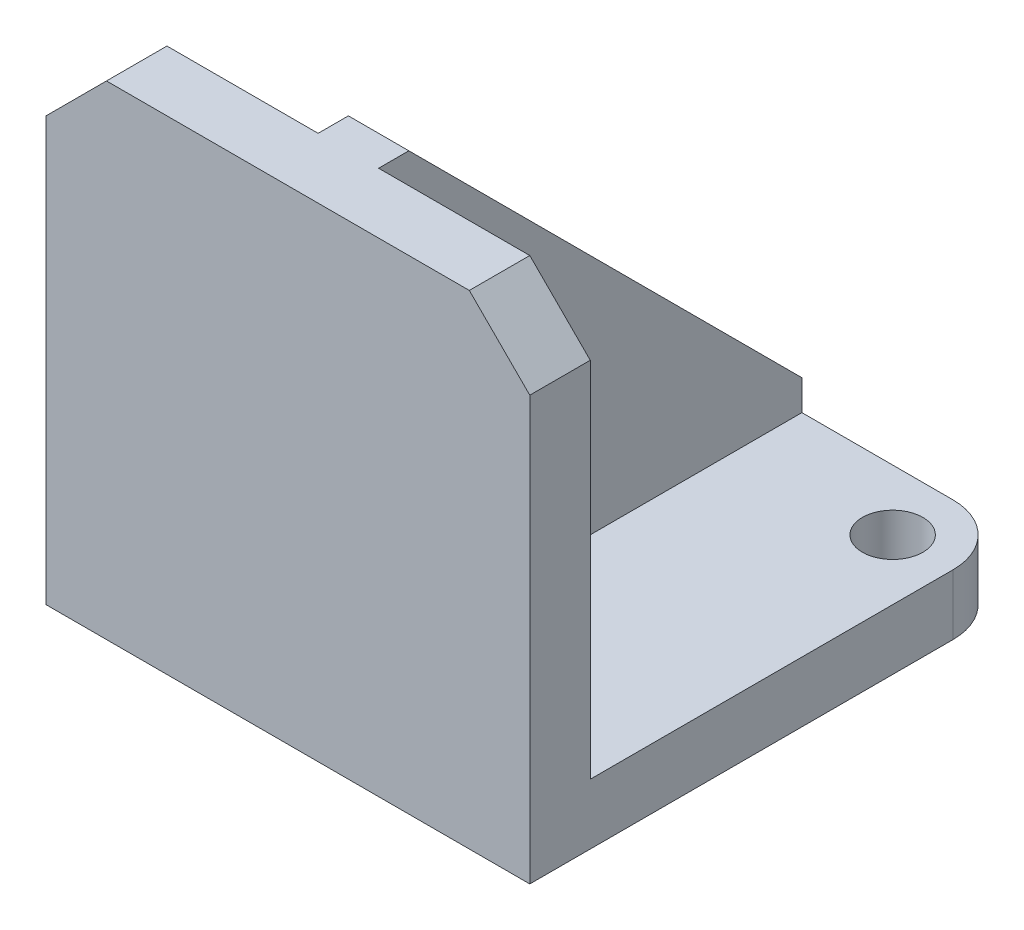
SolidWorks part; units mm, degrees
ref_plane "Front Plane" through (0, 0, 0) normal (0, 0, 1) x (1, 0, 0)
ref_plane "Top Plane" through (0, 0, 0) normal (0, 1, 0) x (1, 0, 0)
ref_plane "Right Plane" through (0, 0, 0) normal (1, 0, 0) x (0, 0, -1)
sketch "Sketch1" plane through (0, 0, 0) normal (1, 0, 0) x (0, 0, -1)
  line L0 (0, 0) -> (80, 0)
  line L1 (0, 80) -> (0, 0)
  line L2 (-13.3901, -27.8014) -> (-13.844, -27.8014)
  line L3 (10, 80) -> (10, 10)
  line L4 (10, 10) -> (80, 10)
  line L5 (0, 80) -> (10, 80)
  line L6 (80, 10) -> (80, 0)
  dimension "D1" = 80
  dimension "D2" = 80
  dimension "D3" = 10
extrude "Boss-Extrude2" add sketch "Sketch1" along normal mid plane 80 contours L3 L4 L6 L0 L1 L5
sketch "Sketch2" plane through (0, 0, 0) normal (1, 0, 0) x (0, 0, -1)
  line L0 (10, 10) -> (80, 10) construction
  line L1 (10, 80) -> (10, 10) construction
  line L2 (10, 10) -> (80, 10)
  line L3 (10, 80) -> (10, 10)
  line L4 (10, 80) -> (15, 80)
  line L5 (15, 80) -> (80, 15)
  line L7 (80, 10) -> (80, 15)
  dimension "D1" = 5
  dimension "D2" = 5
extrude "Boss-Extrude3" add sketch "Sketch2" along normal mid plane 10
fillet "Fillet1" radius 10 2 edges at (-40, 5, -80) (40, 5, -80)
sketch "Sketch3" plane through (0, 10, 0) normal (0, 1, 0) x (1, 0, 0)
  circle A0 centre (30, 70) radius 5
  circle A1 centre (-30, 70) radius 5
  dimension "D1" = 10
  dimension "D2" = 10
extrude "Cut-Extrude1" cut sketch "Sketch3" against normal through all
chamfer "Chamfer1" distance 10 angle 45 2 edges at (40, 80, -5) (-40, 80, -5)
